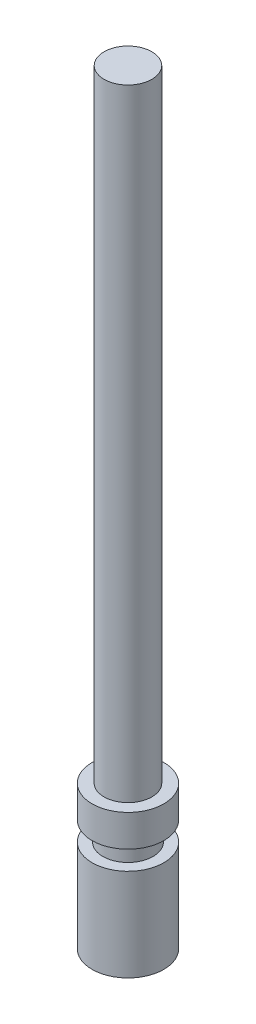
SolidWorks part; units mm, degrees
ref_plane "前视基准面" through (0, 0, 0) normal (0, 0, 1) x (1, 0, 0)
ref_plane "上视基准面" through (0, 0, 0) normal (0, 1, 0) x (1, 0, 0)
ref_plane "右视基准面" through (0, 0, 0) normal (1, 0, 0) x (0, 0, -1)
sketch "草图1" plane through (0, 0, 0) normal (0, 1, 0) x (1, 0, 0)
  circle A0 centre (0, 0) radius 4.5
  dimension "D1" = 9
extrude "凸台-拉伸1" add sketch "草图1" along normal blind 18
sketch "草图2" plane through (0, 0, 0) normal (0, 1, 0) x (1, 0, 0)
  circle A0 centre (0, 0) radius 3
  dimension "D1" = 6
extrude "凸台-拉伸2" add sketch "草图2" along normal blind 96
sketch "草图3" plane through (0, 0, 0) normal (0, 1, 0) x (1, 0, 0)
  circle A0 centre (0, 0) radius 3.15
  dimension "D1" = 6.3
extrude "切除-拉伸1" cut sketch "草图3" along normal blind 2.4 from offset 11.6 flip side to cut
